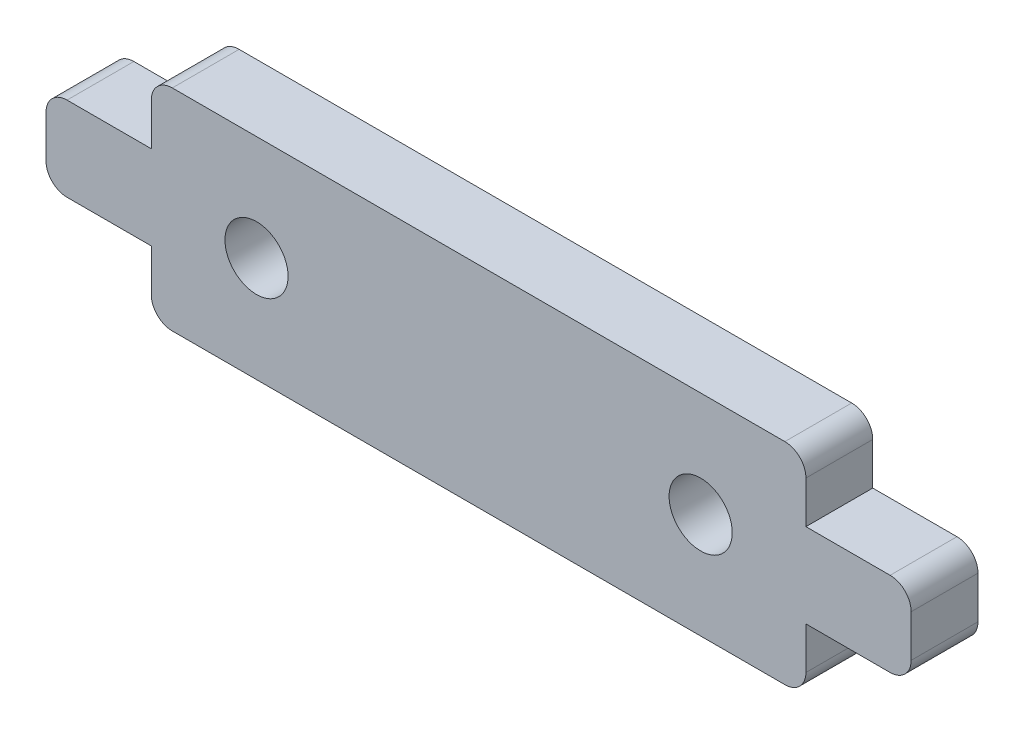
SolidWorks part; units mm, degrees
ref_plane "Front Plane" through (0, 0, 0) normal (0, 0, 1) x (1, 0, 0)
ref_plane "Top Plane" through (0, 0, 0) normal (0, 1, 0) x (1, 0, 0)
ref_plane "Right Plane" through (0, 0, 0) normal (1, 0, 0) x (0, 0, -1)
sketch "Sketch1" plane through (0, 0, 0) normal (0, 0, 1) x (1, 0, 0)
  line L0 (0, 0) -> (4.1573, 0) construction
  line L1 (0, 2) -> (0, -2)
  line L2 (0, -2) -> (5, -2)
  line L3 (5, -2) -> (5, -5)
  line L4 (5, -5) -> (36.1, -5)
  line L5 (36.1, -5) -> (36.1, -2)
  line L6 (36.1, -2) -> (41.1, -2)
  line L7 (41.1, -2) -> (41.1, 2)
  line L8 (36.1, 2) -> (41.1, 2)
  line L9 (36.1, 5) -> (36.1, 2)
  line L10 (5, 5) -> (36.1, 5)
  line L11 (5, 2) -> (5, 5)
  line L12 (0, 2) -> (5, 2)
  point P13 (41.1, 0)
  point P18 (0, 0)
  dimension "D1" = 4
  dimension "D2" = 31.1
  dimension "D3" = 5
  dimension "D4" = 3
extrude "Boss-Extrude1" add sketch "Sketch1" along normal blind 3.175
hole_wizard "Ø3.0mm Dowel Hole1" positions "Sketch2" profile "Sketch3" hole size "Ø3.0" standard "ANSI Metric" end condition up to next
sketch "Sketch2" plane through (0, 0, 3.175) normal (0, 0, 1) x (1, 0, 0)
  line L0 (5, 5) -> (5, 2) construction
  line L1 (36.1, 2) -> (36.1, 5) construction
  point P0 (10, 0)
  point P2 (31.1, 0)
  dimension "D1" = 5
  dimension "D2" = 5
sketch "Sketch3" plane through (10, 0, 3.175) normal (1, 0, 0) x (0, -1, 0)
  line L0 (0, 0) -> (0, 3.175)
  line L1 (0, 3.175) -> (1.5, 3.175)
  line L2 (1.5, 3.175) -> (1.5, 0)
  line L5 (1.5, 0) -> (0, 0)
  line L11 (0, -6.35) -> (0, 107.95) construction
  dimension "Thru Hole Dia." = 3
  dimension "Thru Hole Depth" = 3.175
fillet "Fillet1" radius 1 8 edges at (5, -5, 1.5875) (0, -2, 1.5875) (0, 2, 1.5875) (5, 5, 1.5875) (36.1, 5, 1.5875) (36.1, -5, 1.5875) (41.1, -2, 1.5875) (41.1, 2, 1.5875)
